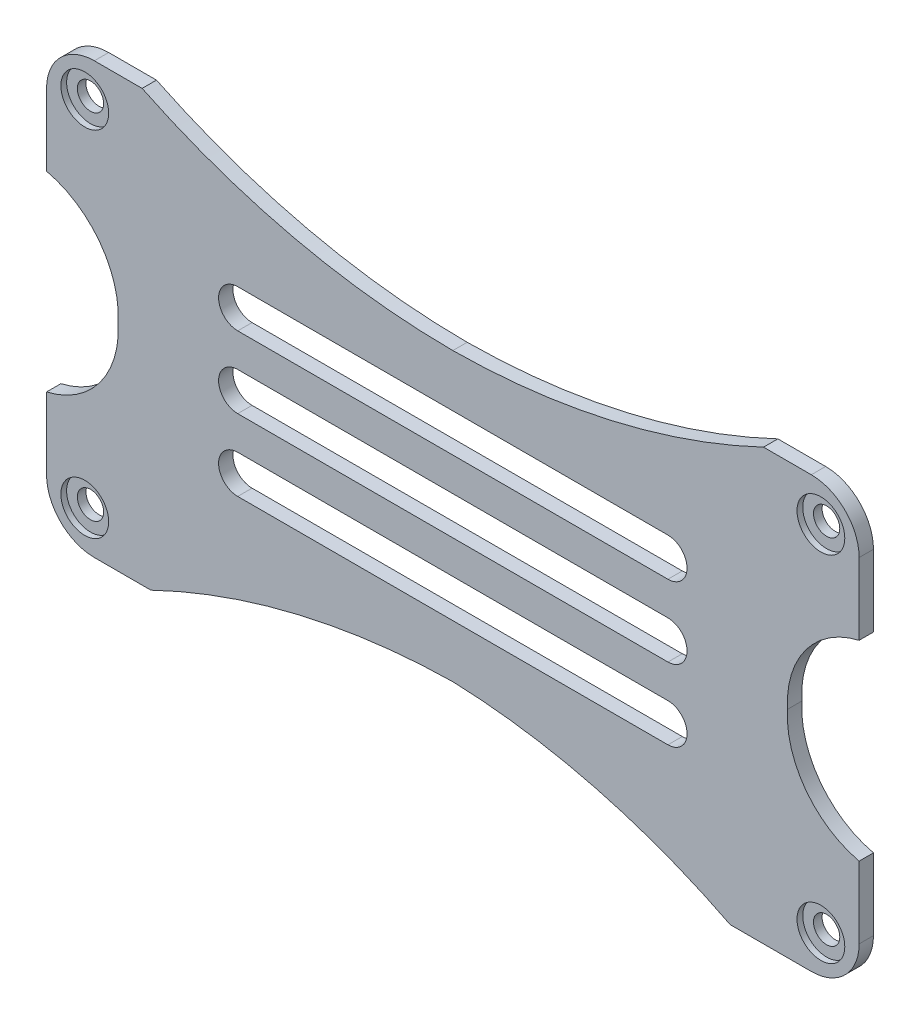
SolidWorks part; units mm, degrees
ref_plane "前视基准面" through (0, 0, 0) normal (0, 0, 1) x (1, 0, 0)
ref_plane "上视基准面" through (0, 0, 0) normal (0, 1, 0) x (1, 0, 0)
ref_plane "右视基准面" through (0, 0, 0) normal (1, 0, 0) x (0, 0, -1)
sketch "草图1" plane through (0, 0, 0) normal (0, 0, 1) x (1, 0, 0)
  line L1 (-72.5741, 45.4874) -> (77.4259, 45.4874)
  line L2 (-82.5741, 35.4874) -> (-82.5741, -34.5126)
  line L3 (-72.5741, -44.5126) -> (77.4259, -44.5126)
  line L4 (87.4259, 35.4874) -> (87.4259, -34.5126)
  arc A0 (-72.5741, 45.4874) -> (-82.5741, 35.4874) centre (-72.5741, 35.4874) ccw
  arc A1 (-72.5741, -44.5126) -> (-82.5741, -34.5126) centre (-72.5741, -34.5126) cw
  arc A2 (87.4259, 35.4874) -> (77.4259, 45.4874) centre (77.4259, 35.4874) ccw
  arc A3 (87.4259, -34.5126) -> (77.4259, -44.5126) centre (77.4259, -34.5126) cw
  dimension "D1" = 10
  dimension "D2" = 10
  dimension "D3" = 10
  dimension "D4" = 10
  dimension "D5" = 90
  dimension "D6" = 170
extrude "凸台-拉伸1" add sketch "草图1" along normal blind 3
ref_plane "for screw hole" through (0, 0, 3) normal (0, 0, 1) x (1, 0, 0)
sketch "草图2" plane through (0, 0, 3) normal (0, 0, 1) x (1, 0, 0)
  line L0 (77.4259, 45.4874) -> (-72.5741, 45.4874) construction
  line L1 (-82.5741, 35.4874) -> (-82.5741, -34.5126) construction
  line L2 (-72.5741, -44.5126) -> (77.4259, -44.5126) construction
  line L3 (87.4259, -34.5126) -> (87.4259, 35.4874) construction
  line L4 (-60.7497, -44.5126) -> (60.4378, -44.5126)
  line L5 (-62.5741, 45.4874) -> (67.4259, 45.4874)
  line L6 (87.4259, 20.4874) -> (87.4259, -19.5126)
  line L7 (-82.5741, 20.4874) -> (-82.5741, -19.5126)
  line L8 (-42.5741, 15.5571) -> (47.4259, 15.5571) construction
  line L9 (-42.5741, 19.5571) -> (47.4259, 19.5571)
  line L10 (-42.5741, 11.5571) -> (47.4259, 11.5571)
  line L11 (-42.5741, 0.5571) -> (47.4259, 0.5571) construction
  line L12 (-42.5741, 4.5571) -> (47.4259, 4.5571)
  line L13 (-42.5741, -3.4429) -> (47.4259, -3.4429)
  line L14 (-42.5741, -14.4429) -> (47.4259, -14.4429) construction
  line L15 (-42.5741, -10.4429) -> (47.4259, -10.4429)
  line L16 (-42.5741, -18.4429) -> (47.4259, -18.4429)
  circle A0 centre (-74.5741, 37.4874) radius 2.75
  circle A1 centre (-74.5741, -36.5126) radius 2.75
  circle A2 centre (79.4259, 37.4874) radius 2.75
  circle A3 centre (79.4259, -36.5126) radius 2.75
  arc A4 (67.4259, 45.4874) -> (2.4259, 30.4874) centre (1.0956, 184.5854) cw
  arc A5 (-62.5741, 45.4874) -> (2.4259, 30.4874) centre (2.8104, 180.4869) ccw
  arc A6 (-60.7497, -44.5126) -> (2.4259, -29.5126) centre (4.6684, -179.4958) cw
  arc A7 (60.4378, -44.5126) -> (2.4259, -29.5126) centre (-2.3985, -167.85) ccw
  arc A8 (87.4259, 20.4874) -> (72.4259, 0.4874) centre (91.8434, 1.5492) ccw
  arc A9 (87.4259, -19.5126) -> (72.4259, 0.4874) centre (91.8434, -0.5745) cw
  arc A10 (-82.5741, 20.4874) -> (-67.5741, 0.4874) centre (-86.9917, 1.5492) cw
  arc A11 (-82.5741, -19.5126) -> (-67.5741, 0.4874) centre (-86.9917, -0.5745) ccw
  arc A12 (-42.5741, 19.5571) -> (-42.5741, 11.5571) centre (-42.5741, 15.5571) ccw
  arc A13 (47.4259, 11.5571) -> (47.4259, 19.5571) centre (47.4259, 15.5571) ccw
  arc A14 (-42.5741, 4.5571) -> (-42.5741, -3.4429) centre (-42.5741, 0.5571) ccw
  arc A15 (47.4259, -3.4429) -> (47.4259, 4.5571) centre (47.4259, 0.5571) ccw
  arc A16 (-42.5741, -10.4429) -> (-42.5741, -18.4429) centre (-42.5741, -14.4429) ccw
  arc A17 (47.4259, -18.4429) -> (47.4259, -10.4429) centre (47.4259, -14.4429) ccw
  point P12 (2.4259, 30.4874)
  point P13 (2.4259, -29.5126)
  point P16 (-62.5741, 45.4874)
  point P17 (67.4259, 45.4874)
  point P18 (-60.7497, -44.5126)
  point P19 (60.4378, -44.5126)
  point P29 (-67.5741, 0.4874)
  point P33 (72.4259, 0.4874)
  point P34 (-82.5741, 20.4874)
  point P35 (-82.5741, -19.5126)
  point P36 (87.4259, -19.5126)
  point P37 (87.4259, 20.4874)
  point P49 (0, 0)
  point P50 (47.4527, 15.2306)
  point P51 (-45.0068, 15.7785)
  point P54 (2.4259, 15.5571)
  point P61 (2.4259, 0.5571)
  point P68 (2.4259, -14.4429)
  dimension "D2" = 5.5
  dimension "D3" = 5.5
  dimension "D4" = 5.5
  dimension "D8" = 8
  dimension "D9" = 8
  dimension "D10" = 8
  dimension "D11" = 5.5
  dimension "D21" = 45
  dimension "D29" = 40
  dimension "D5" = 8
  dimension "D6" = 8
  dimension "D7" = 8
  dimension "D12" = 8
  dimension "D13" = 8
  dimension "D14" = 85
  dimension "D15" = 15
  dimension "D16" = 85
  dimension "D17" = 15
  dimension "D18" = 20
  dimension "D19" = 20
  dimension "D20" = 26.9881
  dimension "D22" = 15
  dimension "D23" = 15
  dimension "D24" = 45
  dimension "D25" = 25
  dimension "D26" = 25
  dimension "D27" = 25
  dimension "D28" = 25
  dimension "D30" = 40
  dimension "D31" = 15
  dimension "D32" = 40
  dimension "D33" = 40
  dimension "D34" = 40
  dimension "D35" = 8
  dimension "D36" = 8
  dimension "D37" = 8
  dimension "D38" = 15
extrude "切除-拉伸1" cut sketch "草图2" against normal blind 10 and the other way blind 42
ref_plane "for outer screw hole" through (0, 0, 3) normal (0, 0, 1) x (1, 0, 0)
sketch "草图3" plane through (0, 0, 3) normal (0, 0, 1) x (1, 0, 0)
  circle A0 centre (-74.5741, 37.4874) radius 5
  circle A1 centre (79.4259, 37.4874) radius 5
  circle A2 centre (79.4259, -36.5126) radius 5
  circle A3 centre (-74.5741, -36.5126) radius 5
  dimension "D1" = 10
  dimension "D2" = 10
  dimension "D3" = 10
  dimension "D4" = 10
extrude "切除-拉伸2" cut sketch "草图3" against normal blind 1.2
